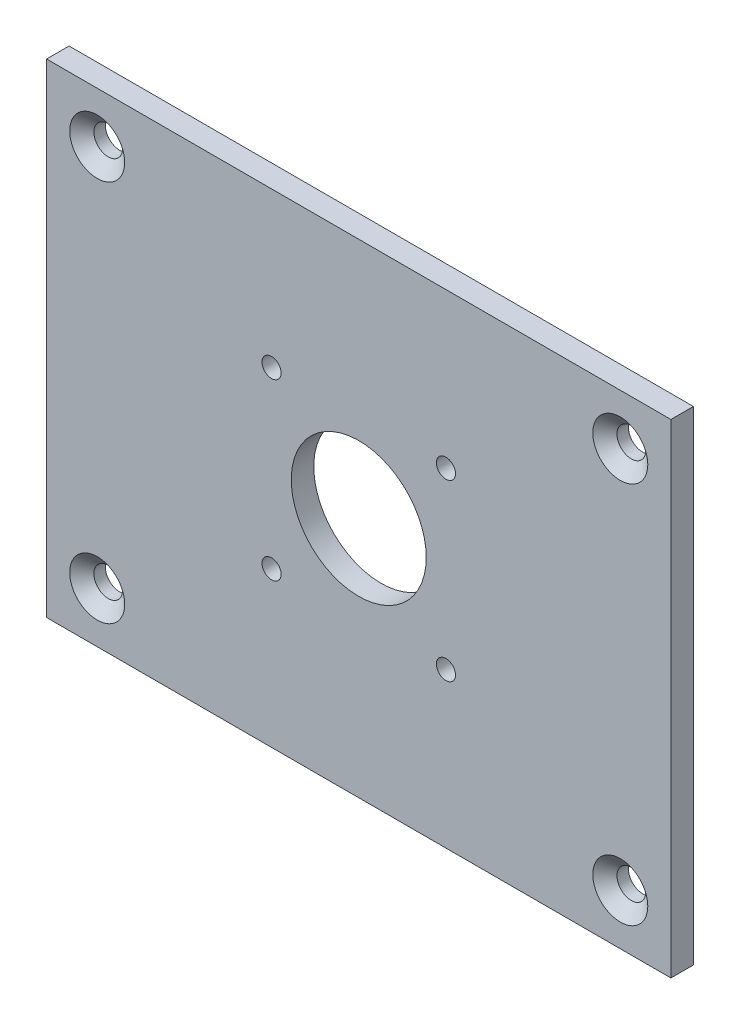
SolidWorks part; units mm, degrees
material "6061-T6 (SS)"
ref_plane "Front Plane" through (0, 0, 0) normal (0, 0, 1) x (1, 0, 0)
ref_plane "Top Plane" through (0, 0, 0) normal (0, 1, 0) x (1, 0, 0)
ref_plane "Right Plane" through (0, 0, 0) normal (1, 0, 0) x (0, 0, -1)
sketch "Sketch1" plane through (0, 0, 0) normal (0, 0, 1) x (1, 0, 0)
  line L1 (0, 0) -> (111, 0)
  line L2 (0, 0) -> (0, 86)
  line L3 (0, 86) -> (111, 86)
  line L4 (111, 0) -> (111, 86)
  dimension "D1" = 111
  dimension "D2" = 86
extrude "base" add sketch "Sketch1" along normal blind 4
sketch "slot outline" plane through (0, 0, 4) normal (0, 0, 1) x (1, 0, 0)
  line L0 (0, 43) -> (18, 43) construction
  line L1 (18, 68) -> (93, 68)
  line L2 (18, 68) -> (18, 18)
  line L3 (18, 18) -> (93, 18)
  line L4 (93, 68) -> (93, 18)
  line L5 (0, 86) -> (0, 0) construction
  line L6 (55.5, 68) -> (55.5, 86) construction
  line L7 (111, 86) -> (0, 86) construction
  dimension "D1" = 50
  dimension "D2" = 75
hole_wizard "nema 17 screw hole pattern" positions "Sketch3" profile "Sketch4" hole size "M3" standard "ANSI Metric" end condition through all
sketch "Sketch3" plane through (0, 0, 4) normal (0, 0, 1) x (1, 0, 0)
  line L1 (40, 58.5) -> (71, 58.5)
  line L2 (40, 58.5) -> (40, 27.5)
  line L3 (40, 27.5) -> (71, 27.5)
  line L4 (71, 58.5) -> (71, 27.5)
  point P1 (40, 58.5)
  point P2 (71, 27.5)
  point P69 (40, 27.5)
  point P70 (71, 58.5)
  point P71 (40, 43)
  point P75 (55.5, 58.5)
  dimension "D1" = 31
sketch "Sketch4" plane through (40, 58.5, 4) normal (1, 0, 0) x (0, -1, 0)
  line L0 (0, 0) -> (0, 4)
  line L1 (0, 4) -> (1.7, 4)
  line L2 (1.7, 4) -> (1.7, 0)
  line L5 (1.7, 0) -> (0, 0)
  line L11 (0, -6.35) -> (0, 107.95) construction
  dimension "Thru Hole Dia." = 3.4
  dimension "Thru Hole Depth" = 4
sketch "Sketch5" plane through (0, 0, 4) normal (0, 0, 1) x (1, 0, 0)
  circle A0 centre (55.5, 43) radius 12
  dimension "D1" = 24
extrude "motor shaft boss cleareance" cut sketch "Sketch5" against normal through all
hole_wizard "wood screw hole pattern" positions "Sketch6" profile "Sketch7" countersink size "#10" standard "ANSI Inch" end condition through all
sketch "Sketch6" plane through (0, 0, 4) normal (0, 0, 1) x (1, 0, 0)
  line L1 (9, 77) -> (102, 77)
  line L2 (9, 77) -> (9, 9)
  line L3 (9, 9) -> (102, 9)
  line L4 (102, 77) -> (102, 9)
  line L8 (9, 43) -> (0, 43)
  line L10 (55.5, 77) -> (55.5, 86)
  point P1 (9, 77)
  point P2 (102, 9)
  point P199 (9, 9)
  point P200 (102, 77)
  dimension "D1" = 9
  dimension "D2" = 9
sketch "Sketch7" plane through (9, 77, 4) normal (1, 0, 0) x (0, -1, 0)
  line L0 (0, 0) -> (0, 4)
  line L1 (0, 4) -> (2.5527, 4)
  line L2 (2.5527, 4) -> (2.5527, 1.9608)
  line L3 (2.5527, 1.9608) -> (4.8895, 0)
  line L5 (4.8895, 0) -> (0, 0)
  line L6 (-2.5527, 1.9608) -> (-4.8895, 0) construction
  line L11 (0, -6.35) -> (0, 107.95) construction
  dimension "Thru Hole Dia." = 5.1054
  dimension "Thru Hole Depth" = 4
  dimension "Near C'Sink Dia." = 9.779
  dimension "Near C'Sink Angle" = 100
equation "\"board_thickness\" = 18mm"
equation "\"way_width\"= 75mm"
equation "\"way_thickness\"= 50mm"
equation "\"radial_clearance\"= 0.1mm"
equation "\"slider_width\"= \"way_width\"-2* \"radial_clearance\" - 2*0.65"
equation "\"slider_thickness\" = \"way_thickness\" - 2 * \"radial_clearance\""
equation "\"column_width\"= \"way_width\" + 2 * \"board_thickness\""
equation "\"boxway_slot_width\" = 50mm"
equation "\"keeper_rail_width\" = (\"column_width\" - \"boxway_slot_width\")/2"
equation "\"slider_length\" = 125mm"
equation "\"nut_diameter\"= 22mm"
equation "\"nut_length\"= 15mm"
equation "\"leadscrew_diameter\"= 10mm"
equation "\"leadscrew_radial_clearance\"= 1mm"
equation "\"bearing_bolt_pattern_width\" = 30mm"
equation "\"bearing_bolt_pattern_height\" = 75mm"
equation "\"desktop_bolt_pattern_width\" = 30mm"
equation "\"desktop_bolt_pattern_height\" = 30mm"
equation "\"bearing_bolt_nut_counterbore_diameter\" = 12mm"
equation "\"bearing_bolt_nut_counterbore_depth\"= 10mm"
equation "\"desktop_depth\"= 500mm"
equation "\"desktop_width\"= 650mm"
equation "\"desktop_thickness\"= 18mm"
equation "\"leg_height\"=100mm"
equation "\"leg_width\"=18mm"
equation "\"leg_length\"=500mm"
equation "\"lap_joint_height\" = 50mm"
equation "\"lap_dowel_diameter\"= 8mm"
equation "\"lap_dowel_hole_z_spacing\"=30"
equation "\"D1@Sketch1\"=\"column_width\""
equation "\"D2@Sketch1\"=2*\"board_thickness\"+\"way_thickness\""
equation "\"D1@slot outline\" = \"way_thickness\""
equation "\"D2@slot outline\" = \"way_width\""
equation "\"D2@Sketch6\"=0.5 * \"board_thickness\""
